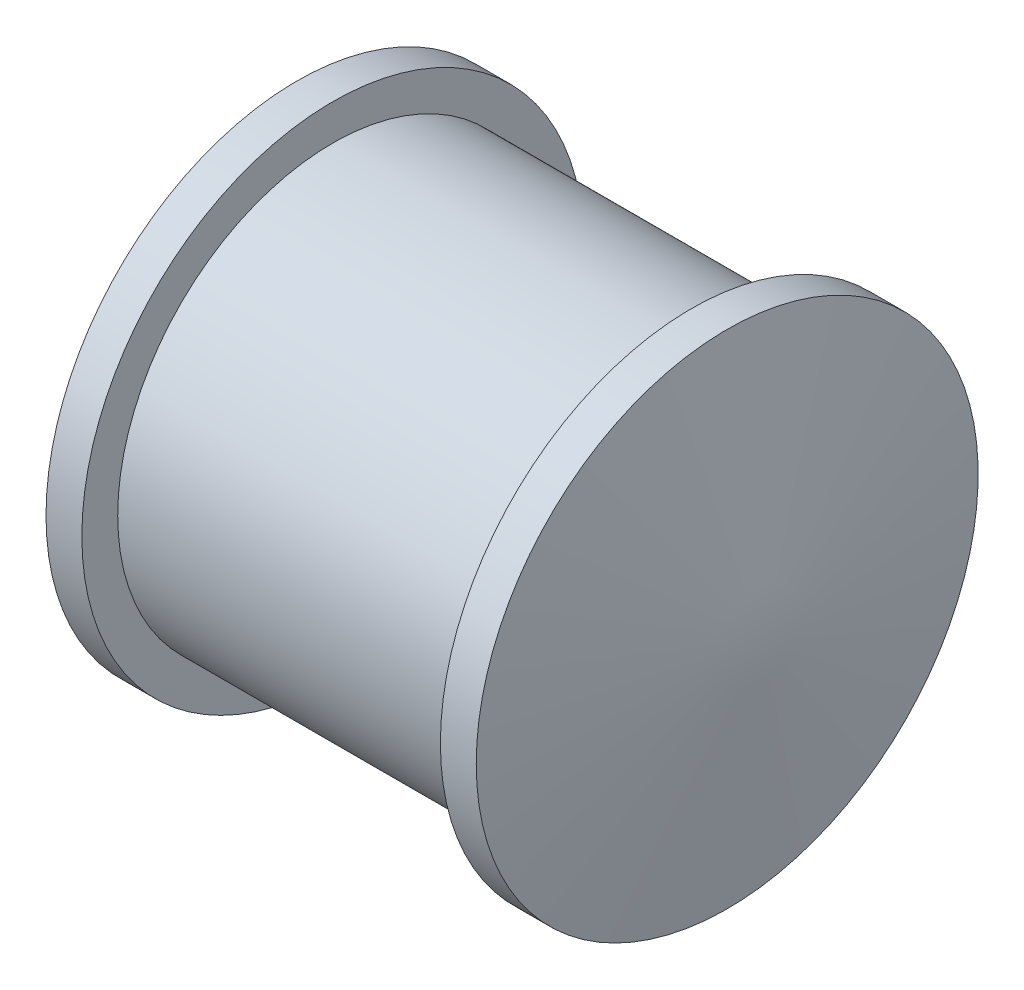
SolidWorks part; units mm, degrees
ref_plane "前视基准面" through (0, 0, 0) normal (0, 0, 1) x (1, 0, 0)
ref_plane "上视基准面" through (0, 0, 0) normal (0, 1, 0) x (1, 0, 0)
ref_plane "右视基准面" through (0, 0, 0) normal (1, 0, 0) x (0, 0, -1)
sketch "草图1" plane through (0, 0, 0) normal (0, 0, 1) x (1, 0, 0)
  line L0 (3, 3.5) -> (3.5, 0)
  line L1 (0, 0) -> (2.5, 0)
  line L2 (0, 0) -> (0, 3)
  line L3 (0, 3) -> (2.5, 3)
  line L4 (2.5, 0) -> (2.5, 3)
  line L5 (2.5, 0) -> (3, 0)
  line L6 (2.5, 0) -> (2.5, 3.5)
  line L7 (2.5, 3.5) -> (3, 3.5)
  line L8 (3, 0) -> (3, 3.5)
  line L9 (3.5, 0) -> (3, 0)
  dimension "D1" = 0.5
  dimension "D2" = 2.5
  dimension "D3" = 0.5
  dimension "D4" = 3
  dimension "D5" = 3.5
revolve "旋转1" add sketch "草图1" angle 360 about L1
mirror "镜向1" about plane through (0, 0, 0) normal (-1, 0, 0) of "旋转1"
